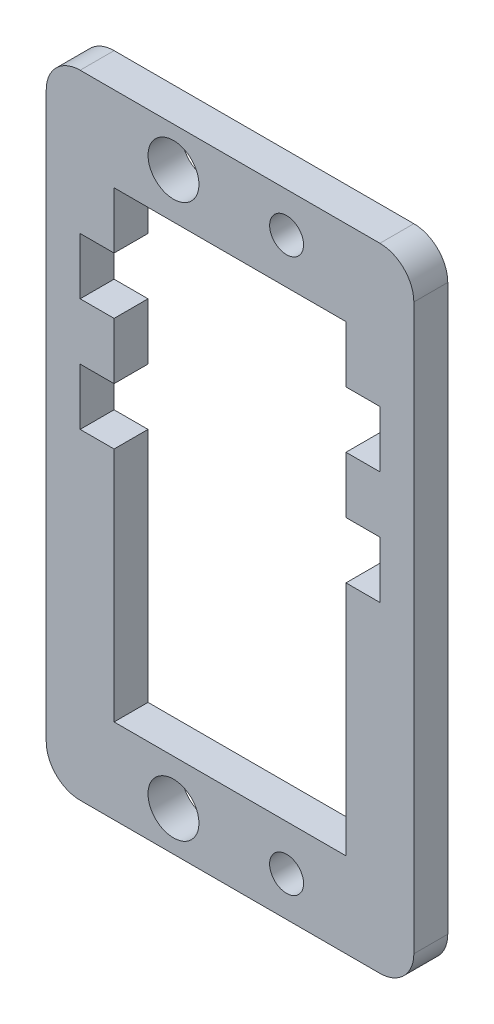
SolidWorks part; units mm, degrees
ref_plane "Alzado" through (0, 0, 0) normal (0, 0, 1) x (1, 0, 0)
ref_plane "Planta" through (0, 0, 0) normal (0, 1, 0) x (1, 0, 0)
ref_plane "Vista lateral" through (0, 0, 0) normal (1, 0, 0) x (0, 0, -1)
sketch "Sketch1" plane through (0, 0, 0) normal (0, 0, 1) x (1, 0, 0)
  line L0 (-13.25, 27.95) -> (13.25, 27.95)
  line L1 (-10.25, 20.45) -> (10.25, 20.45)
  line L2 (-10.25, 20.45) -> (-10.25, 15.45)
  line L3 (-10.25, -20.45) -> (10.25, -20.45)
  line L4 (10.25, 20.45) -> (10.25, 15.45)
  line L5 (-10.25, 20.45) -> (10.25, -20.45) construction
  line L6 (-10.25, -20.45) -> (10.25, 20.45) construction
  line L7 (16.25, 24.95) -> (16.25, -24.95)
  line L8 (13.25, -27.95) -> (-13.25, -27.95)
  line L9 (-16.25, -24.95) -> (-16.25, 24.95)
  line L10 (0, 27.95) -> (0, -27.95) construction
  line L11 (16.25, 0) -> (-16.25, 0) construction
  line L12 (-10.25, 15.45) -> (-13.25, 15.45)
  line L13 (-13.25, 15.45) -> (-13.25, 10.45)
  line L14 (-13.25, 10.45) -> (-10.25, 10.45)
  line L15 (-10.25, 5.45) -> (-13.25, 5.45)
  line L16 (-13.25, 5.45) -> (-13.25, 0.45)
  line L17 (-13.25, 0.45) -> (-10.25, 0.45)
  line L18 (10.25, 15.45) -> (13.25, 15.45)
  line L19 (13.25, 15.45) -> (13.25, 10.45)
  line L20 (13.25, 10.45) -> (10.25, 10.45)
  line L21 (10.25, 5.45) -> (13.25, 5.45)
  line L22 (13.25, 5.45) -> (13.25, 0.45)
  line L23 (13.25, 0.45) -> (10.25, 0.45)
  line L24 (-10.25, 10.45) -> (-10.25, 5.45)
  line L25 (-10.25, 0.45) -> (-10.25, -20.45)
  line L26 (10.25, 0.45) -> (10.25, -20.45)
  line L27 (10.25, 10.45) -> (10.25, 5.45)
  line L28 (-5, 24.45) -> (5, 24.45) construction
  arc A0 (13.25, 27.95) -> (16.25, 24.95) centre (13.25, 24.95) cw
  arc A1 (16.25, -24.95) -> (13.25, -27.95) centre (13.25, -24.95) cw
  arc A2 (-13.25, -27.95) -> (-16.25, -24.95) centre (-13.25, -24.95) cw
  arc A3 (-16.25, 24.95) -> (-13.25, 27.95) centre (-13.25, 24.95) cw
  circle A4 centre (-5, 24.45) radius 2.25
  circle A5 centre (5, 24.45) radius 1.5
  circle A6 centre (5, -24.45) radius 1.5
  circle A7 centre (-5, -24.45) radius 2.25
  point P0 (0, 0)
  point P22 (0, 0)
  dimension "D4" = 3
  dimension "D14" = 4.5
  dimension "D15" = 3
  dimension "D1" = 20.5
  dimension "D2" = 40.9
  dimension "D3" = 7.5
  dimension "D5" = 6
  dimension "D6" = 3
  dimension "D7" = 3
  dimension "D8" = 5
  dimension "D9" = 5
  dimension "D10" = 5
  dimension "D11" = 5
  dimension "D12" = 4
  dimension "D13" = 10
extrude "Boss-Extrude1" add sketch "Sketch1" along normal blind 3
